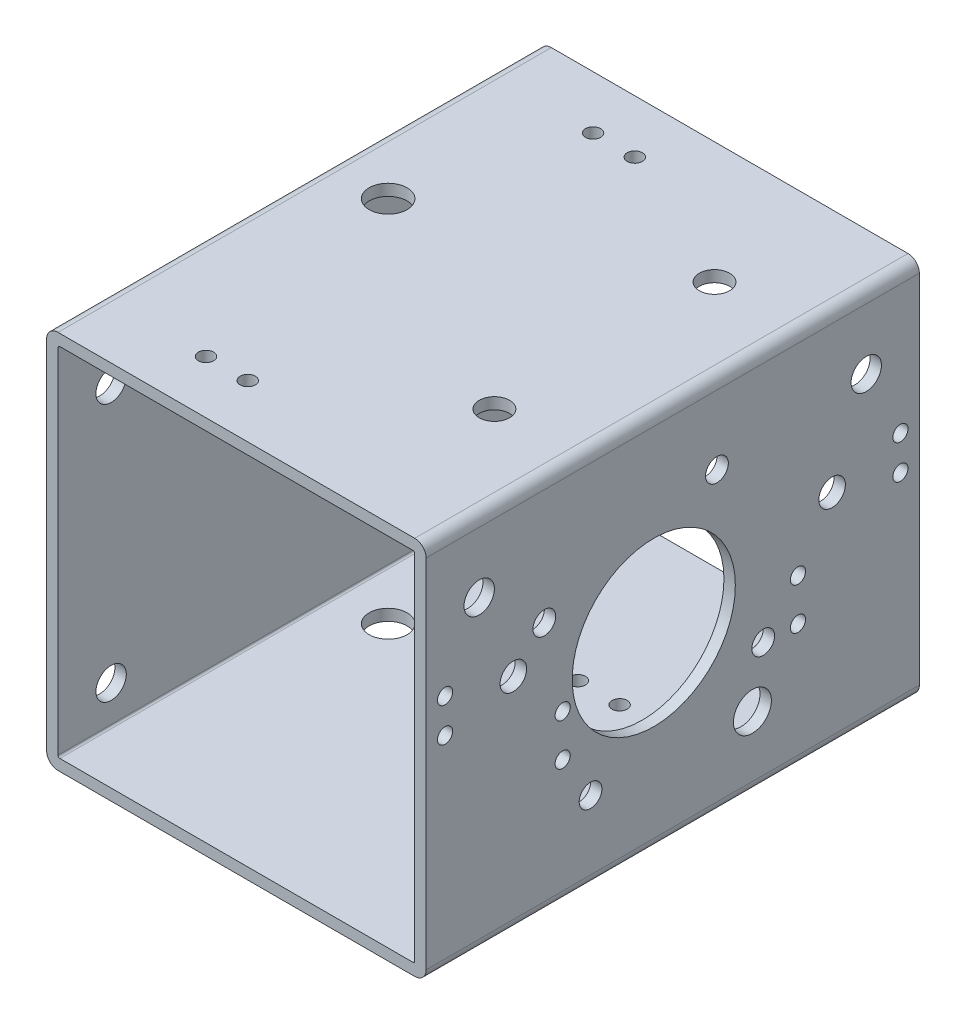
SolidWorks part; units mm, degrees
ref_plane "Front Plane" through (0, 0, 0) normal (0, 0, 1) x (1, 0, 0)
ref_plane "Top Plane" through (0, 0, 0) normal (0, 1, 0) x (1, 0, 0)
ref_plane "Right Plane" through (0, 0, 0) normal (1, 0, 0) x (0, 0, -1)
sketch "Sketch1" plane through (0, 0, 0) normal (0, 0, 1) x (1, 0, 0)
  line L1 (-50, 50) -> (50, 50)
  line L2 (-50, 50) -> (-50, -50)
  line L3 (-50, -50) -> (50, -50)
  line L4 (50, 50) -> (50, -50)
  line L5 (-50, 50) -> (50, -50) construction
  line L6 (-50, -50) -> (50, 50) construction
  point P0 (0, 0)
  dimension "D1" = 100
  dimension "D2" = 100
extrude "Extrude-Thin1" add sketch "Sketch1" along normal blind 130 thin
fillet "Fillet1" radius 0.5 4 edges at (-47, -47, 65) (-47, 47, 65) (47, 47, 65) (47, -47, 65)
fillet "Fillet2" radius 3 4 edges at (50, -50, 65) (-50, -50, 65) (50, 50, 65) (-50, 50, 65)
sketch "Holes - top" plane through (0, 0, 0) normal (0, 1, 0) x (1, 0, 0)
  line L0 (-3, 0) -> (-3, -130) construction
  line L1 (47, -130) -> (-47, -130) construction
  line L2 (-23, 0) -> (-23, -130) construction
  line L3 (47, 0) -> (-47, 0) construction
  line L4 (17, 0) -> (17, -130) construction
  circle A0 centre (-34, -56) radius 11 construction
  circle A1 centre (28, -90) radius 11 construction
  circle A2 centre (28, -32) radius 11 construction
  dimension "D4" = 22
  dimension "D1" = 40
  dimension "D2" = 40
  dimension "D3" = 32
  dimension "D5" = 56
  dimension "D6" = 3
hole_wizard "Ø8.0 (8) Diameter Hole2" positions "Sketch6" profile "Sketch5" hole size "Ø8.0" standard "ANSI Metric" end condition through all
sketch "Sketch6" plane through (0, 50, 0) normal (0, 1, 0) x (1, 0, 0)
  point P0 (28, -32)
  point P6 (28, -90)
sketch "Sketch5" plane through (28, 50, 32) normal (1, 0, 0) x (0, 0, 1)
  line L0 (0, 0) -> (0, 100)
  line L1 (0, 100) -> (4, 100)
  line L2 (4, 100) -> (4, 0)
  line L5 (4, 0) -> (0, 0)
  line L11 (0, -6.35) -> (0, 107.95) construction
  dimension "Thru Hole Dia." = 8
  dimension "Thru Hole Depth" = 100
sketch "Holes - side" plane through (0, 0, 0) normal (1, 0, 0) x (0, 0, -1)
  line L0 (0, 0) -> (-130, 0) construction
  line L1 (-130, -47) -> (-130, 47) construction
  line L2 (-130, 20) -> (0, 20) construction
  line L3 (0, -47) -> (0, 47) construction
  line L4 (-130, -20) -> (0, -20) construction
  circle A0 centre (-116, 31) radius 11 construction
  circle A1 centre (-14, 31) radius 11 construction
  circle A2 centre (-44, -31) radius 11 construction
  dimension "D1" = 40
  dimension "D2" = 22
  dimension "D3" = 14
  dimension "D4" = 14
  dimension "D5" = 44
hole_wizard "Ø8.0 (8) Diameter Hole3" positions "Sketch9" profile "Sketch8" hole size "Ø8.0" standard "ANSI Metric" end condition through all
sketch "Sketch9" plane through (50, 0, 0) normal (1, 0, 0) x (0, 0, -1)
  point P0 (-14, 31)
  point P3 (-116, 31)
sketch "Sketch8" plane through (50, 31, 14) normal (0, 1, 0) x (0, 0, -1)
  line L0 (0, 0) -> (0, 100)
  line L1 (0, 100) -> (4, 100)
  line L2 (4, 100) -> (4, 0)
  line L5 (4, 0) -> (0, 0)
  line L11 (0, -6.35) -> (0, 107.95) construction
  dimension "Thru Hole Dia." = 8
  dimension "Thru Hole Depth" = 100
hole_wizard "Ø10.0 (10) Diameter Hole1" positions "Sketch12" profile "Sketch11" hole size "Ø10.0" standard "ANSI Metric" end condition through all
sketch "Sketch12" plane through (0, 50, 0) normal (0, 1, 0) x (1, 0, 0)
  point P0 (-34, -56)
sketch "Sketch11" plane through (-34, 50, 56) normal (1, 0, 0) x (0, 0, 1)
  line L0 (0, 0) -> (0, 100)
  line L1 (0, 100) -> (5, 100)
  line L2 (5, 100) -> (5, 0)
  line L5 (5, 0) -> (0, 0)
  line L11 (0, -6.35) -> (0, 107.95) construction
  dimension "Thru Hole Dia." = 10
  dimension "Thru Hole Depth" = 100
hole_wizard "Ø10.0 (10) Diameter Hole2" positions "Sketch14" profile "Sketch13" hole size "Ø10.0" standard "ANSI Metric" end condition through all
sketch "Sketch14" plane through (50, 0, 0) normal (1, 0, 0) x (0, 0, -1)
  point P0 (-44, -31)
sketch "Sketch13" plane through (50, -31, 44) normal (0, 1, 0) x (0, 0, -1)
  line L0 (0, 0) -> (0, 100)
  line L1 (0, 100) -> (5, 100)
  line L2 (5, 100) -> (5, 0)
  line L5 (5, 0) -> (0, 0)
  line L11 (0, -6.35) -> (0, 107.95) construction
  dimension "Thru Hole Dia." = 10
  dimension "Thru Hole Depth" = 100
sketch "Holes - Nema 23 motor" plane through (0, 0, 0) normal (1, 0, 0) x (0, 0, -1)
  line L0 (-98.8427, 16.6524) -> (-53.3476, 28.8427) construction
  line L1 (-98.8427, 16.6524) -> (-86.6524, -28.8427) construction
  line L2 (-53.3476, 28.8427) -> (-41.1573, -16.6524) construction
  line L3 (-86.6524, -28.8427) -> (-41.1573, -16.6524) construction
  line L4 (-98.8427, 16.6524) -> (-41.1573, -16.6524) construction
  line L5 (-53.3476, 28.8427) -> (-86.6524, -28.8427) construction
  line L6 (0, 0) -> (-130, 0) construction
  point P1 (-70, 0)
  dimension "D1" = 70
  dimension "D2" = 47.1
  dimension "D3" = 47.1
  dimension "D4" = 15
hole_wizard "Ø21.0 (21) Diameter Hole1" positions "Sketch24" profile "Sketch23" hole size "Ø21.0" standard "ANSI Metric"
sketch "Sketch24" plane through (50, 0, 0) normal (1, 0, 0) x (0, 0, -1)
  point P0 (-70, 0)
sketch "Sketch23" plane through (50, 0, 70) normal (0, 1, 0) x (0, 0, -1)
  line L0 (0, 0) -> (0, 3)
  line L1 (0, 3) -> (21.5, 3)
  line L2 (21.5, 3) -> (21.5, 0)
  line L5 (21.5, 0) -> (0, 0)
  line L11 (0, -6.35) -> (0, 107.95) construction
  dimension "Thru Hole Dia." = 43
  dimension "Thru Hole Depth" = 3
hole_wizard "Ø6.0 (6) Diameter Hole1" positions "Sketch26" profile "Sketch25" hole size "Ø6.0" standard "ANSI Metric"
sketch "Sketch26" plane through (50, 0, 0) normal (1, 0, 0) x (0, 0, -1)
  point P0 (-41.1573, -16.6524)
  point P3 (-53.3476, 28.8427)
  point P6 (-98.8427, 16.6524)
  point P9 (-86.6524, -28.8427)
sketch "Sketch25" plane through (50, -16.6524, 41.1573) normal (0, 1, 0) x (0, 0, -1)
  line L0 (0, 0) -> (0, 3)
  line L1 (0, 3) -> (3, 3)
  line L2 (3, 3) -> (3, 0)
  line L5 (3, 0) -> (0, 0)
  line L11 (0, -6.35) -> (0, 107.95) construction
  dimension "Thru Hole Dia." = 6
  dimension "Thru Hole Depth" = 3
sketch "Sketch27" plane through (50, 0, 0) normal (1, 0, 0) x (0, 0, -1)
  line L1 (0, -47) -> (0, 47) construction
  line L2 (-130, 50) -> (0, 50) construction
  line L3 (-65, 66.9997) -> (-65, -40.3101) construction
  line L4 (-130, -47) -> (-130, 47) construction
  circle A0 centre (-5, 13) radius 2
  circle A1 centre (-5, 4) radius 2
  circle A2 centre (-23, 8.5) radius 3.5
  circle A3 centre (-107, 8.5) radius 3.5
  circle A4 centre (-125, 4) radius 2
  circle A5 centre (-125, 13) radius 2
  dimension "D1" = 4
  dimension "D2" = 9
  dimension "D3" = 5
  dimension "D4" = 46
  dimension "D7" = 18
  dimension "D8" = 4.5
  dimension "D9" = 7
  dimension "D5" = 0
  dimension "D6" = 65
extrude "Cut-Extrude1" cut sketch "Sketch27" against normal up to next
sketch "Sketch31" plane through (-50, 0, 0) normal (-1, 0, 0) x (0, 0, 1)
  line L0 (0, 47) -> (0, -47) construction
  line L1 (130, 47) -> (130, -47) construction
  line L2 (0, -47) -> (130, -47) construction
  circle A0 centre (14, -37) radius 4
  circle A1 centre (116, -37) radius 4
  dimension "D1" = 8
  dimension "D2" = 8
  dimension "D3" = 14
  dimension "D4" = 14
  dimension "D5" = 10
extrude "Cut-Extrude2" cut sketch "Sketch31" against normal up to next
sketch "Sketch34" plane through (0, 50, 0) normal (0, 1, 0) x (1, 0, 0)
  line L0 (47, 0) -> (-47, 0) construction
  line L1 (-50, -130) -> (-50, 0) construction
  line L2 (-50, -65) -> (-126.2259, -65) construction
  circle A0 centre (-22, -14) radius 2
  circle A1 centre (-11, -14) radius 2
  circle A2 centre (-11, -116) radius 2
  circle A3 centre (-22, -116) radius 2
  dimension "D1" = 14
  dimension "D2" = 28
  dimension "D3" = 4
  dimension "D4" = 39
  dimension "D5" = 65
extrude "Cut-Extrude3" cut sketch "Sketch34" against normal blind 10
sketch "Sketch35" plane through (0, -50, 0) normal (0, -1, 0) x (1, 0, 0)
  line L0 (-47, 0) -> (47, 0) construction
  line L1 (50, 130) -> (50, 0) construction
  circle A0 centre (15, 44) radius 2
  circle A1 centre (4, 44) radius 2
  dimension "D1" = 4
  dimension "D2" = 44
  dimension "D3" = 35
  dimension "D4" = 11
extrude "Cut-Extrude4" cut sketch "Sketch35" against normal blind 10
sketch "Sketch36" plane through (-50, 0, 0) normal (-1, 0, 0) x (0, 0, 1)
  line L0 (130, 47) -> (130, -47) construction
  line L1 (0, 50) -> (130, 50) construction
  circle A0 centre (56, 19) radius 2
  circle A1 centre (56, 8) radius 2
  dimension "D1" = 4
  dimension "D2" = 74
  dimension "D3" = 31
  dimension "D4" = 11
extrude "Cut-Extrude5" cut sketch "Sketch36" against normal blind 10
sketch "Sketch37" plane through (50, 0, 0) normal (1, 0, 0) x (0, 0, -1)
  line L0 (0, -50) -> (-130, -50) construction
  line L1 (0, -47) -> (0, 47) construction
  line L2 (-130, -47) -> (-130, 47) construction
  circle A0 centre (-32, -17) radius 2
  circle A1 centre (-32, -6) radius 2
  circle A2 centre (-94, -6) radius 2
  circle A3 centre (-94, -17) radius 2
  dimension "D1" = 4
  dimension "D2" = 33
  dimension "D3" = 32
  dimension "D4" = 11
  dimension "D5" = 36
extrude "Cut-Extrude6" cut sketch "Sketch37" against normal blind 10
sketch "Sketch38" plane through (0, -50, 0) normal (0, -1, 0) x (1, 0, 0)
  line L0 (-47, 0) -> (47, 0) construction
  line L1 (50, 130) -> (50, 0) construction
  circle A0 centre (38, 44) radius 3.1
  circle A1 centre (-19, 44) radius 3.1
  dimension "D1" = 44
  dimension "D2" = 12
  dimension "D3" = 57
  dimension "D4" = 6.2
extrude "Cut-Extrude7" cut sketch "Sketch38" against normal blind 10
sketch "Sketch39" plane through (-50, 0, 0) normal (-1, 0, 0) x (0, 0, 1)
  line L0 (0, 50) -> (130, 50) construction
  line L1 (0, 47) -> (0, -47) construction
  circle A0 centre (56, 35) radius 3.1
  circle A1 centre (56, -15) radius 3.1
  dimension "D1" = 15
  dimension "D2" = 50
  dimension "D3" = 56
  dimension "D4" = 6.2
extrude "Cut-Extrude8" cut sketch "Sketch39" against normal blind 10
equation "\"L\"= 130"
equation "\"D1@Extrude-Thin1\"=\"L\""
equation "\"d-bearing\"= 22'diameter of bearing"
equation "\"D4@Holes - top\"=\"d-bearing\""
equation "\"D2@Holes - side\"=\"d-bearing\""
